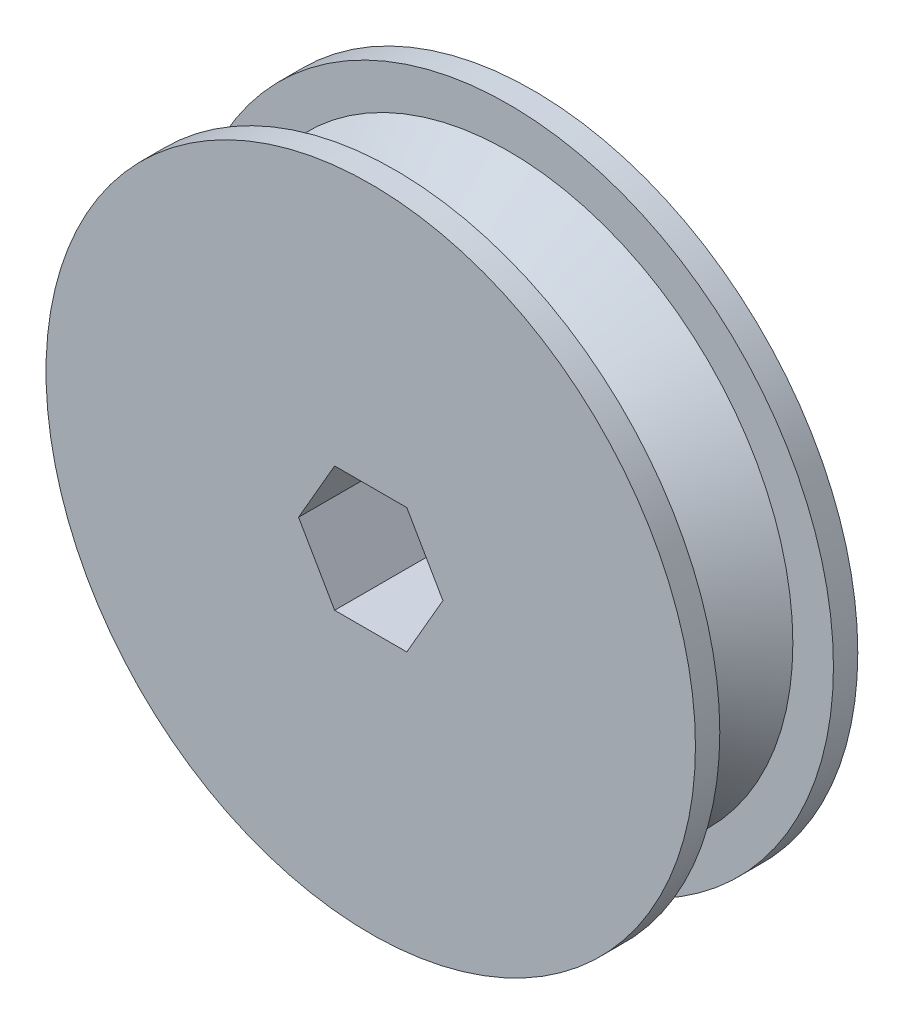
SolidWorks part; units mm, degrees
ref_plane "Front Plane" through (0, 0, 0) normal (0, 0, 1) x (1, 0, 0)
ref_plane "Top Plane" through (0, 0, 0) normal (0, 1, 0) x (1, 0, 0)
ref_plane "Right Plane" through (0, 0, 0) normal (1, 0, 0) x (0, 0, -1)
sketch "Sketch1" plane through (0, 0, 0) normal (0, 0, 1) x (1, 0, 0)
  circle A0 centre (0, 0) radius 25.4
  dimension "D1" = 50.8
extrude "Boss-Extrude1" add sketch "Sketch1" along normal mid plane 12.7
sketch "Sketch3" plane through (0, 0, 0) normal (0, 1, 0) x (1, 0, 0)
  line L0 (-25.4, 6.35) -> (-25.4, -6.35) construction
  line L1 (-25.4, 4.445) -> (-25.4, -4.445)
  line L2 (-22.225, 4.445) -> (-25.4, 4.445)
  line L3 (-22.225, -4.445) -> (-25.4, -4.445)
  line L4 (-22.225, -4.445) -> (-17.78, 0)
  line L5 (-17.78, 0) -> (-22.225, 4.445)
  line L6 (-25.4, -6.35) -> (25.4, -6.35) construction
  dimension "D1" = 8.89
  dimension "D2" = 3.175
  dimension "D3" = 4.445
  dimension "D4" = 4.445
  dimension "D5" = 3.175
  dimension "D6" = 1.905
ref_axis "Axis1" through (0, 0, 17.1197) along (0, 0, -1)
revolve "Cut-Revolve1" cut sketch "Sketch3" angle 360 about axis through (0, 0, 17.1197) along (0, 0, -1)
sketch "Sketch4" plane through (0, 0, -6.35) normal (0, 0, -1) x (-1, 0, 0)
  line L0 (5.6459, 0) -> (2.823, 4.8895)
  line L1 (2.823, 4.8895) -> (-2.823, 4.8895)
  line L2 (-2.823, 4.8895) -> (-5.6459, 0)
  line L3 (-5.6459, 0) -> (-2.823, -4.8895)
  line L4 (-2.823, -4.8895) -> (2.823, -4.8895)
  line L5 (2.823, -4.8895) -> (5.6459, 0)
  point P2 (0, 4.8895)
  dimension "D1" = 9.779
  dimension "D2" = 9.779
  dimension "D3" = 9.779
  dimension "D4" = 4.8895
  dimension "D5" = 120
extrude "Cut-Extrude1" cut sketch "Sketch4" against normal through all
